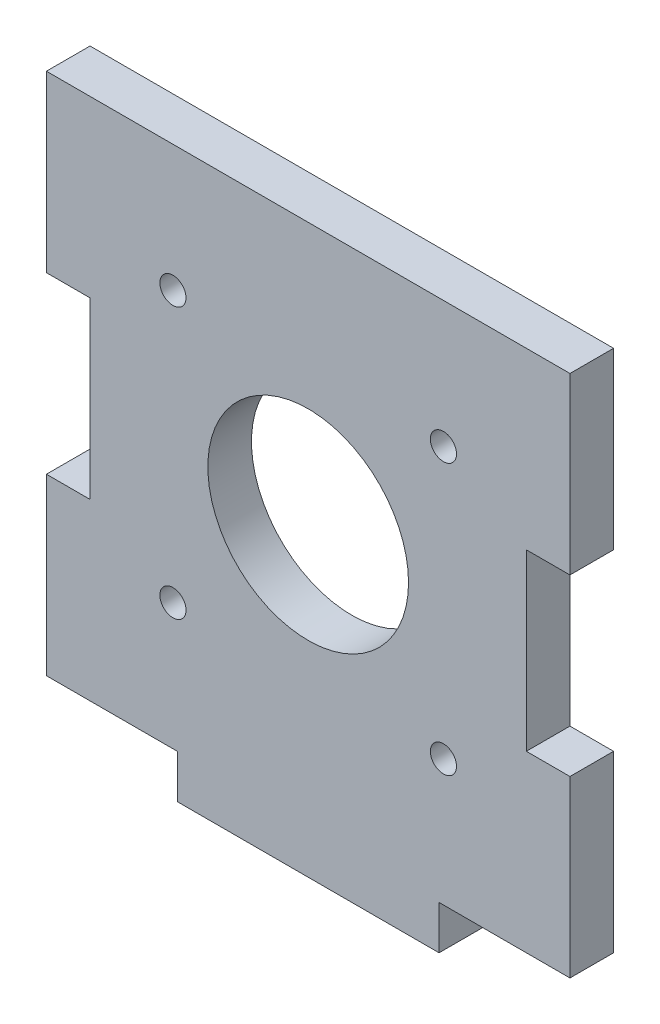
SolidWorks part; units mm, degrees
ref_plane "前视基准面" through (0, 0, 0) normal (0, 0, 1) x (1, 0, 0)
ref_plane "上视基准面" through (0, 0, 0) normal (0, 1, 0) x (1, 0, 0)
ref_plane "右视基准面" through (0, 0, 0) normal (1, 0, 0) x (0, 0, -1)
sketch "草图1" plane through (0, 0, 0) normal (0, 0, 1) x (1, 0, 0)
  line L0 (0, 40) -> (0, 60)
  line L1 (0, 0) -> (15, 0)
  line L2 (0, 0) -> (0, 20)
  line L3 (0, 60) -> (60, 60)
  line L4 (60, 0) -> (60, 20)
  line L5 (60, 40) -> (60, 60)
  line L6 (15, 0) -> (15, -5)
  line L7 (15, -5) -> (45, -5)
  line L8 (45, 0) -> (45, -5)
  line L9 (0, 40) -> (5, 40)
  line L10 (45, 0) -> (60, 0)
  line L11 (0, 20) -> (5, 20)
  line L12 (5, 40) -> (5, 20)
  line L13 (60, 40) -> (55, 40)
  line L14 (30, 65.6077) -> (30, -18.5627) construction
  line L15 (60, 20) -> (55, 20)
  line L16 (55, 40) -> (55, 20)
  line L17 (-21.147, 30) -> (97.0782, 30) construction
  line L19 (14.5, 45.5) -> (45.5, 45.5) construction
  line L20 (14.5, 45.5) -> (14.5, 14.5) construction
  line L21 (14.5, 14.5) -> (45.5, 14.5) construction
  line L22 (45.5, 45.5) -> (45.5, 14.5) construction
  line L23 (14.5, 45.5) -> (45.5, 14.5) construction
  line L24 (14.5, 14.5) -> (45.5, 45.5) construction
  circle A0 centre (30, 30) radius 11.5
  circle A1 centre (14.5, 45.5) radius 1.5
  circle A2 centre (45.5, 45.5) radius 1.5
  circle A3 centre (45.5, 14.5) radius 1.5
  circle A4 centre (14.5, 14.5) radius 1.5
  dimension "D13" = 23
  dimension "D1" = 60
  dimension "D2" = 60
  dimension "D3" = 30
  dimension "D4" = 5
  dimension "D5" = 15
  dimension "D6" = 5
  dimension "D7" = 5
  dimension "D8" = 20
  dimension "D9" = 20
  dimension "D10" = 20
  dimension "D11" = 30
  dimension "D12" = 30
  dimension "D14" = 31
extrude "凸台-拉伸1" add sketch "草图1" along normal blind 5
